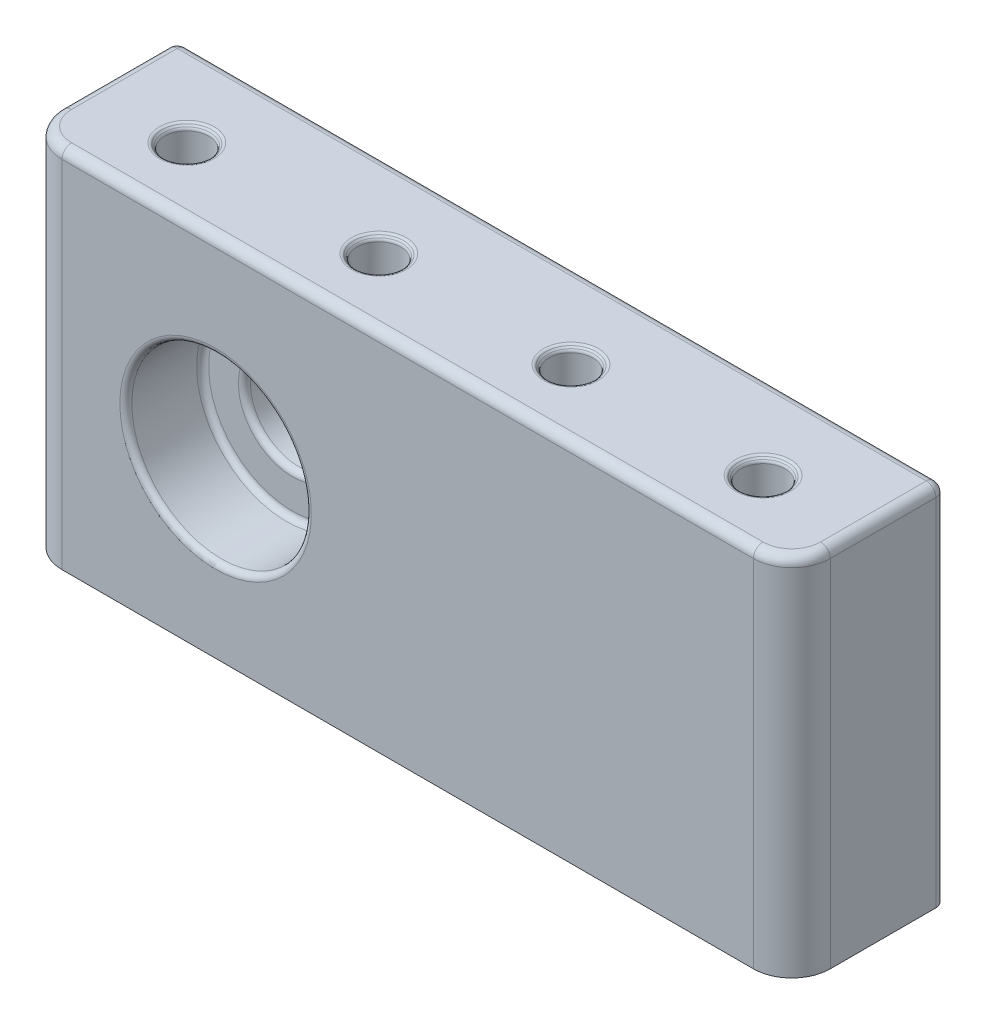
SolidWorks part; units mm, degrees
ref_plane "Front Plane" through (0, 0, 0) normal (0, 0, 1) x (1, 0, 0)
ref_plane "Top Plane" through (0, 0, 0) normal (0, 1, 0) x (1, 0, 0)
ref_plane "Right Plane" through (0, 0, 0) normal (1, 0, 0) x (0, 0, -1)
sketch "Sketch2" plane through (0, 0, 0) normal (0, 0, 1) x (1, 0, 0)
  line L1 (-20, -9.5) -> (20, -9.5)
  line L2 (-20, -9.5) -> (-20, 9.5)
  line L3 (-20, 9.5) -> (20, 9.5)
  line L4 (20, -9.5) -> (20, 9.5)
  line L5 (-20, -9.5) -> (20, 9.5) construction
  line L6 (-20, 9.5) -> (20, -9.5) construction
  point P0 (0, 0)
  dimension "D1" = 40
  dimension "D2" = 19
extrude "Boss-Extrude1" add sketch "Sketch2" along normal blind 8
fillet "Fillet1" radius 2 2 edges at (20, 0, 8) (-20, 0, 8)
sketch "Sketch5" plane through (0, 9.5, 0) normal (0, 1, 0) x (1, 0, 0)
  line L0 (18, -8) -> (-18, -8) construction
  line L1 (-20, -6) -> (-20, 0) construction
  circle A0 centre (-15, -4.5) radius 1.15
  circle A1 centre (-5, -4.5) radius 1.15
  circle A2 centre (5, -4.5) radius 1.15
  circle A3 centre (15, -4.5) radius 1.15
  dimension "D1" = 2.3
  dimension "D2" = 3.5
  dimension "D3" = 5
  dimension "D5" = 10
  dimension "D4" = 4
extrude "Cut-Extrude3" cut sketch "Sketch5" against normal blind 7
chamfer "Chamfer1" distance 0.2 angle 45 8 edges at (15, 9.5, 5.65) (15, 2.5, 5.65) (5, 9.5, 5.65) (5, 2.5, 5.65) (-5, 9.5, 5.65) (-5, 2.5, 5.65) (-15, 9.5, 5.65) (-15, 2.5, 5.65)
fillet "Fillet3" radius 0.2 8 edges at (-15, 9.3, 3.35) (-15, 9.5, 3.15) (-5, 9.3, 3.35) (-5, 9.5, 3.15) (5, 9.3, 3.35) (5, 9.5, 3.15) (15, 9.3, 3.35) (15, 9.5, 3.15)
fillet "Fillet2" radius 0.5 8 edges at (20, 9.5, 3) (19.4142, 9.5, 7.4142) (-20, 9.5, 3) (-19.4142, 9.5, 7.4142) (0, 9.5, 8) (0, 9.5, 0) (20, 0, 0) (-20, 0, 0)
sketch "Sketch3" plane through (0, 0, 8) normal (0, 0, 1) x (1, 0, 0)
  line L0 (-18, -9.5) -> (18, -9.5) construction
  line L1 (-20, -9.5) -> (-20, 9) construction
  circle A0 centre (-10, -0.5) radius 4.675
  dimension "D1" = 9.35
  dimension "D2" = 9
  dimension "D3" = 10
extrude "Cut-Extrude1" cut sketch "Sketch3" against normal blind 4
sketch "Sketch4" plane through (0, 0, 4) normal (0, 0, 1) x (1, 0, 0)
  circle A0 centre (-10, -0.5) radius 2.5
  circle A1 centre (-10, -0.5) radius 4.675 construction
  dimension "D1" = 5
extrude "Cut-Extrude2" cut sketch "Sketch4" against normal blind 4
chamfer "Chamfer2" distance 1.5 angle 45 1 edges at (-7.5, -0.5, 0)
fillet "Fillet4" radius 0.3125 5 edges at (-5.325, -0.5, 4) (-5.325, -0.5, 8) (-7.5, -0.5, 4) (-14, -0.5, 0) (-12.5, -0.5, 1.5)
